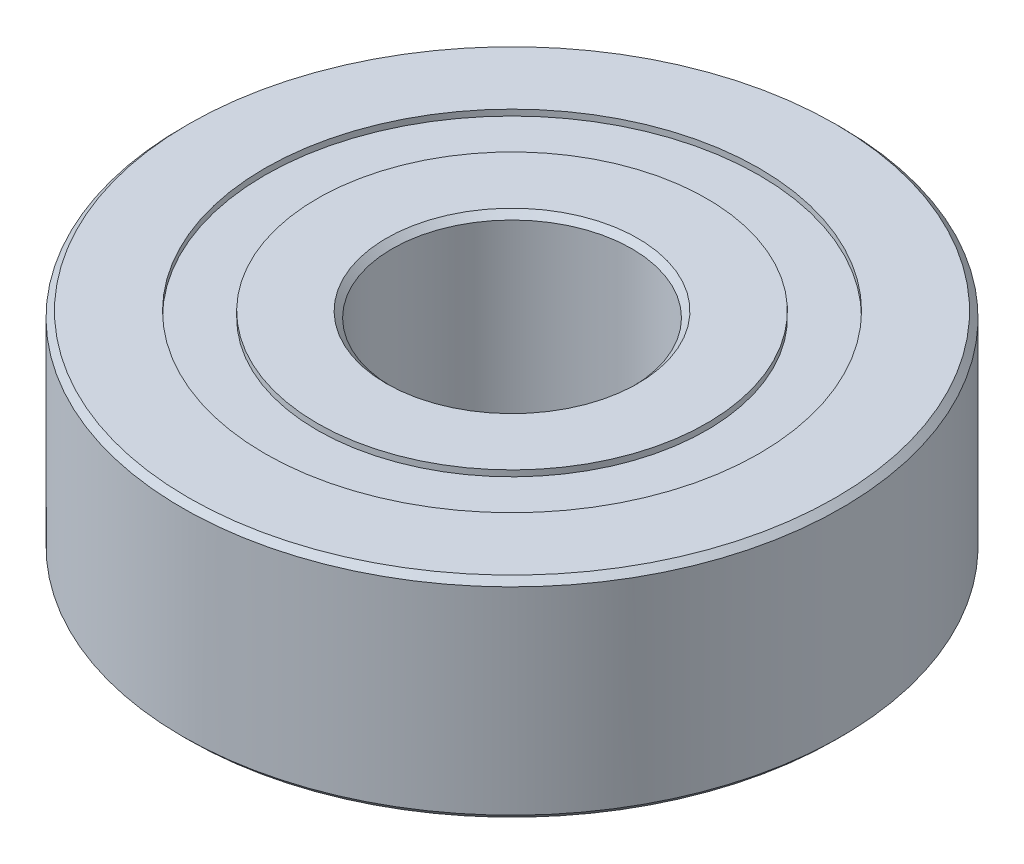
SolidWorks part; units mm, degrees
material "Alloy Steel"
ref_plane "Front Plane" through (0, 0, 0) normal (0, 0, 1) x (1, 0, 0)
ref_plane "Top Plane" through (0, 0, 0) normal (0, 1, 0) x (1, 0, 0)
ref_plane "Right Plane" through (0, 0, 0) normal (1, 0, 0) x (0, 0, -1)
sketch "Sketch1" plane through (0, 0, 0) normal (0, 1, 0) x (1, 0, 0)
  circle A0 centre (0, 0) radius 11
  circle A1 centre (0, 0) radius 4
  dimension "D1" = 22
  dimension "D2" = 8
extrude "Boss-Extrude1" add sketch "Sketch1" along normal blind 7
sketch "Sketch2" plane through (0, 7, 0) normal (0, 1, 0) x (1, 0, 0)
  circle A0 centre (0, 0) radius 6.5
  circle A1 centre (0, 0) radius 8.25
  dimension "D1" = 16.5
  dimension "D2" = 13
extrude "Cut-Extrude1" cut sketch "Sketch2" against normal blind 0.2
sketch "Sketch3" plane through (0, 0, 0) normal (0, -1, 0) x (1, 0, 0)
  circle A0 centre (0, 0) radius 6.5 construction
  circle A1 centre (0, 0) radius 8.25
  circle A2 centre (0, 0) radius 8.25
  circle A3 centre (0, 0) radius 6.5
  dimension "D1" = 0
extrude "Cut-Extrude2" cut sketch "Sketch3" against normal blind 0.2
chamfer "Chamfer1" distance 0.2 angle 45 4 edges at (0, 7, 11) (0, 0, 11) (0, 7, 4) (0, 0, 4)
